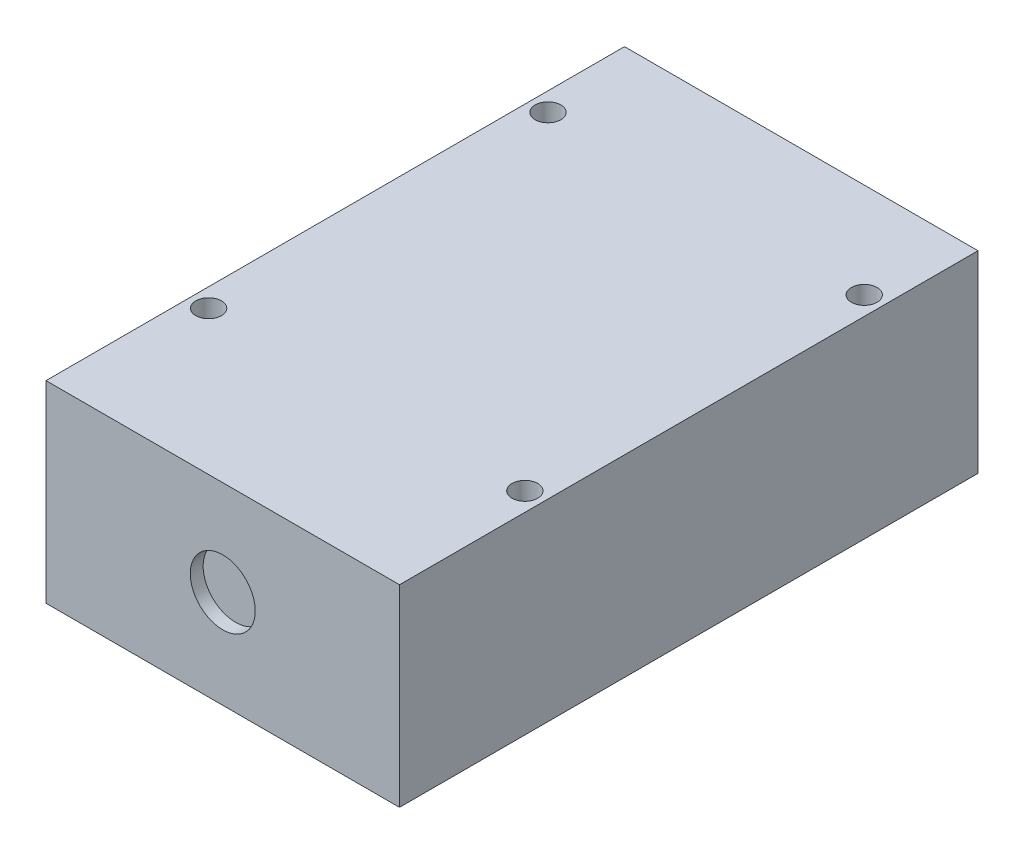
SolidWorks part; units mm, degrees
ref_plane "前视基准面" through (0, 0, 0) normal (0, 0, 1) x (1, 0, 0)
ref_plane "上视基准面" through (0, 0, 0) normal (0, 1, 0) x (1, 0, 0)
ref_plane "右视基准面" through (0, 0, 0) normal (1, 0, 0) x (0, 0, -1)
other "Configuration Table"
sketch "草图1" plane through (0, 0, 0) normal (0, 1, 0) x (1, 0, 0)
  line L0 (0, 36.7107) -> (0, -31.7036) construction
  line L1 (-13.75, 22.5) -> (13.75, 22.5)
  line L2 (-13.75, 22.5) -> (-13.75, -22.5)
  line L3 (-13.75, -22.5) -> (13.75, -22.5)
  line L4 (13.75, 22.5) -> (13.75, -22.5)
  line L5 (-13.75, 22.5) -> (13.75, -22.5) construction
  line L6 (-13.75, -22.5) -> (13.75, 22.5) construction
  circle A0 centre (-12.3, 15.1) radius 1
  circle A1 centre (12.3, 15.1) radius 1
  circle A2 centre (12.3, -11.3) radius 1
  circle A3 centre (-12.3, -11.3) radius 1
  point P0 (0, 0)
  dimension "D3" = 2
  dimension "D1" = 27.5
  dimension "D2" = 45
  dimension "D4" = 24.6
  dimension "D5" = 26.4
  dimension "D6" = 33.8
extrude "凸台-拉伸1" add sketch "草图1" along normal blind 15
sketch "草图2" plane through (0, 0, 22.5) normal (0, 0, 1) x (1, 0, 0)
  circle A0 centre (0, 7.6149) radius 2.5265
extrude "切除-拉伸1" cut sketch "草图2" against normal blind 1
